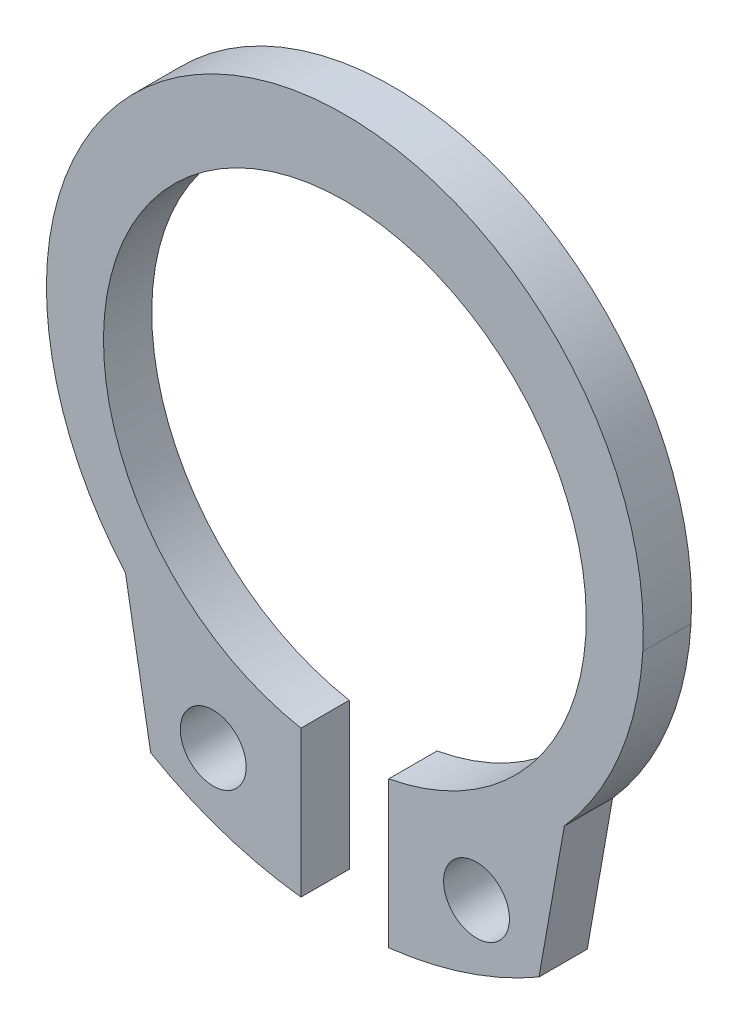
SolidWorks part; units mm, degrees
ref_plane "前视基准面" through (0, 0, 0) normal (0, 0, 1) x (1, 0, 0)
ref_plane "上视基准面" through (0, 0, 0) normal (0, 1, 0) x (1, 0, 0)
ref_plane "右视基准面" through (0, 0, 0) normal (1, 0, 0) x (0, 0, -1)
sketch "草图1" plane through (0, 0, 0) normal (0, 0, 1) x (1, 0, 0)
  line L0 (0, -55) -> (0, 55) construction
  line L1 (0, 0) -> (0, -19.7203) construction
  line L2 (-8.7671, 0) -> (12.6095, 0) construction
  line L3 (55, 0) -> (-55, 0) construction
  line L4 (-5, -4.3396) -> (-4.4238, -7.6072)
  line L5 (5, -4.3396) -> (4.4238, -7.6072)
  circle A3 centre (0, 0) radius 5.5
  arc A4 (6.7882, 0) -> (-6.7882, 0) centre (0, 0.4) ccw
  arc A5 (-6.7882, 0) -> (-5, -4.3396) centre (0.3993, 0.4235) ccw
  arc A6 (-4.4238, -7.6072) -> (4.4238, -7.6072) centre (0, 0) ccw
  arc A7 (6.7882, 0) -> (5, -4.3396) centre (-0.3993, 0.4235) cw
  point P17 (0, -12.1227)
  dimension "D1" = 11
  dimension "D2" = 13.6
  dimension "D4" = 7.2
  dimension "D7" = 8.8
  dimension "D3" = 0.4
  dimension "D5" = 10
  dimension "D6" = 10
extrude "凸台-拉伸1" add sketch "草图1" along normal blind 1.1
sketch "草图2" plane through (0, 0, 1.1) normal (0, 0, 1) x (1, 0, 0)
  line L0 (0, -4.6247) -> (0, -13.3705)
  line L1 (0, -0.605) -> (0, 0.605) construction
extrude "切除-拉伸-薄壁1" cut sketch "草图2" against normal blind 1.1 and the other way through all thin thin type mid plane wall 2
sketch "草图3" plane through (0, 0, 1.1) normal (0, 0, 1) x (1, 0, 0)
  line L0 (0, -0.6271) -> (0, -19.0231) construction
  line L1 (0, -0.605) -> (0, 0.605) construction
  circle A0 centre (3, -6.8015) radius 0.75
  circle A1 centre (-3, -6.8015) radius 0.75
  point P9 (-2.3052, -7.6406)
  point P10 (-3, -6.8015)
  dimension "D1" = 1.5
  dimension "D2" = 1.5
  dimension "D3" = 3
  dimension "D4" = 3
extrude "切除-拉伸1" cut sketch "草图3" against normal through all
